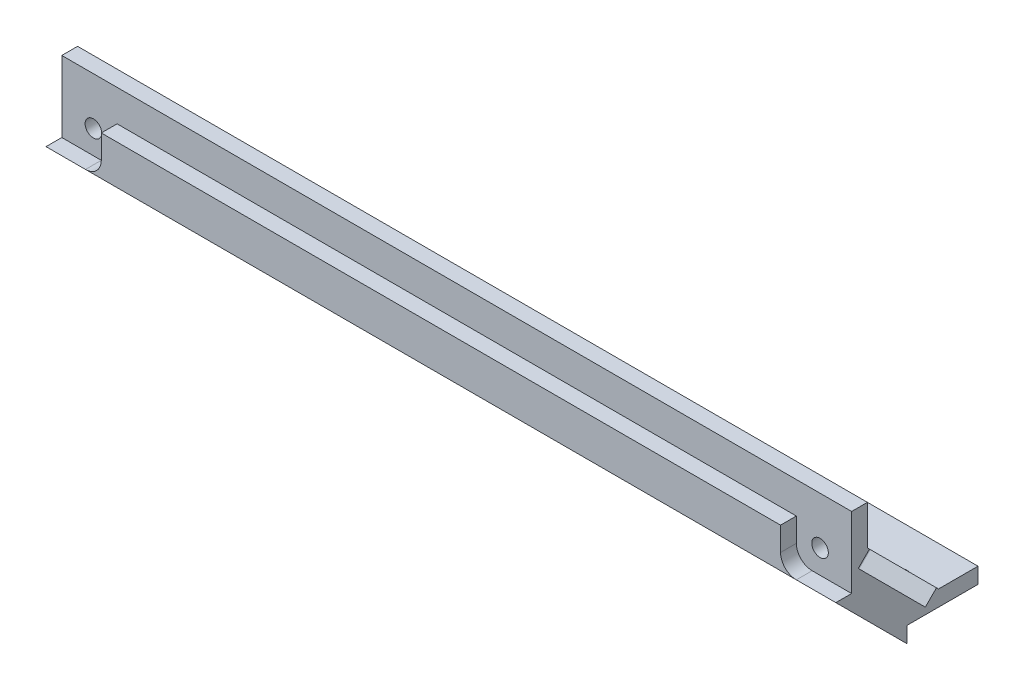
SolidWorks part; units mm, degrees
ref_plane "Front Plane" through (0, 0, 0) normal (0, 0, 1) x (1, 0, 0)
ref_plane "Top Plane" through (0, 0, 0) normal (0, 1, 0) x (1, 0, 0)
ref_plane "Right Plane" through (0, 0, 0) normal (1, 0, 0) x (0, 0, -1)
sketch "Sketch5" plane through (0, 0, 0) normal (1, 0, 0) x (0, 0, -1)
  line L0 (0, 0) -> (0, 36)
  line L1 (0, 36) -> (8, 36)
  line L5 (36, 8) -> (36, 0)
  line L6 (36, 0) -> (0, 0)
  line L7 (8, 36) -> (8, 8)
  line L8 (8, 8) -> (36, 8)
  dimension "D1" = 8
  dimension "D2" = 8
  dimension "D3" = 36
  dimension "D4" = 36
extrude "Boss-Extrude3" add sketch "Sketch5" along normal blind 200
chamfer "Chamfer2" distance 18 angle 45 1 edges at (100, 8, -8)
chamfer "Chamfer3" distance 18 angle 45 1 edges at (100, 0, 0)
sketch "Sketch6" plane through (0, 0, 0) normal (0, -1, 0) x (-1, 0, 0)
  line L1 (-200, 28) -> (0, 28)
  line L2 (-200, 28) -> (-200, 36)
  line L3 (-200, 36) -> (0, 36)
  line L4 (0, 28) -> (0, 36)
  dimension "D1" = 8
extrude "Cut-Extrude2" cut sketch "Sketch6" against normal blind 4
sketch "Sketch7" plane through (0, 0, 0) normal (0, 0, 1) x (1, 0, 0)
  line L1 (200, 36) -> (0, 36)
  line L2 (200, 36) -> (200, 28)
  line L3 (200, 28) -> (0, 28)
  line L4 (0, 36) -> (0, 28)
  dimension "D1" = 8
extrude "Cut-Extrude3" cut sketch "Sketch7" against normal blind 4
sketch "Sketch8" plane through (0, 17, -17) normal (0, 0.7071, -0.7071) x (-1, 0, 0)
  line L0 (-182.5, 0) -> (-167.5, 0) construction
  circle A0 centre (-182.5, 0) radius 1.4
  circle A1 centre (-167.5, 0) radius 1.4
  circle A2 centre (-152.5, 0) radius 1.4
  circle A3 centre (-137.5, 0) radius 1.4
  circle A4 centre (-122.5, 0) radius 1.4
  circle A5 centre (-107.5, 0) radius 1.4
  circle A6 centre (-92.5, 0) radius 1.4
  circle A7 centre (-77.5, 0) radius 1.4
  circle A8 centre (-62.5, 0) radius 1.4
  circle A9 centre (-47.5, 0) radius 1.4
  circle A10 centre (-32.5, 0) radius 1.4
  circle A11 centre (-17.5, 0) radius 1.4
  dimension "D1" = 2.8
  dimension "D2" = 182.5
  dimension "D4" = 15
  dimension "D3" = 12
extrude "Cut-Extrude4" cut sketch "Sketch8" against normal blind 3
sketch "Sketch9" plane through (0, 17, -17) normal (0, 0.7071, -0.7071) x (-1, 0, 0)
  circle A0 centre (-73, -10) radius 2.1
  circle A1 centre (-127, -10) radius 2.1
  circle A2 centre (-127, 10) radius 2.1
  circle A3 centre (-73, 10) radius 2.1
  dimension "D1" = 4.2
  dimension "D2" = 54
  dimension "D3" = 73
  dimension "D4" = 10
  dimension "D5" = 20
extrude "Cut-Extrude5" cut sketch "Sketch9" against normal blind 6
sketch "Sketch10" plane through (0, 17, -17) normal (0, 0.7071, -0.7071) x (-1, 0, 0)
  circle A0 centre (-89, -10) radius 2.1
  circle A1 centre (-111, -10) radius 2.1
  circle A2 centre (-111, 10) radius 2.1
  circle A3 centre (-89, 10) radius 2.1
  dimension "D3" = 4.2
  dimension "D1" = 22
  dimension "D2" = 20
  dimension "D4" = 10
  dimension "D5" = 89
extrude "Cut-Extrude6" cut sketch "Sketch10" against normal blind 6
sketch "Sketch11" plane through (0, 17, -17) normal (0, 0.7071, -0.7071) x (-1, 0, 0)
  line L0 (0, -12) -> (-14, 0)
  line L1 (-14, 0) -> (0, 12)
  line L2 (0, 12) -> (0, -12)
  line L3 (-200, 12) -> (-186, 0)
  line L4 (-186, 0) -> (-200, -12)
  line L5 (-200, -12) -> (-200, 12)
  dimension "D1" = 14
  dimension "D2" = 12
  dimension "D3" = 12
  dimension "D4" = 12
  dimension "D5" = 12
  dimension "D6" = 12
  dimension "D7" = 12
  dimension "D8" = 14
extrude "Cut-Extrude7" cut sketch "Sketch11" against normal blind 4
sketch "Sketch12" plane through (200, 0, 0) normal (1, 0, 0) x (0, 0, -1)
  line L1 (0, 28) -> (4, 28)
  line L2 (0, 28) -> (0, 18)
  line L3 (0, 18) -> (4, 18)
  line L4 (4, 28) -> (4, 18)
  line L5 (28, 0) -> (18, 0)
  line L6 (28, 0) -> (28, 4)
  line L7 (28, 4) -> (18, 4)
  line L8 (18, 0) -> (18, 4)
  dimension "D1" = 4
  dimension "D2" = 10
  dimension "D3" = 10
  dimension "D4" = 4
extrude "Cut-Extrude8" cut sketch "Sketch12" against normal blind 14
fillet "Fillet1" radius 4 2 edges at (14, 15.5858, -15.5858) (186, 15.5858, -15.5858)
fillet "Fillet2" radius 4 2 edges at (186, 2, -18) (186, 18, -2)
sketch "Sketch13" plane through (0, 0, 0) normal (-1, 0, 0) x (0, 0, 1)
  line L1 (-4, 28) -> (0, 28)
  line L2 (-4, 28) -> (-4, 18)
  line L3 (-4, 18) -> (0, 18)
  line L4 (0, 28) -> (0, 18)
  line L5 (-28, 0) -> (-18, 0)
  line L6 (-28, 0) -> (-28, 4)
  line L7 (-28, 4) -> (-18, 4)
  line L8 (-18, 0) -> (-18, 4)
  dimension "D1" = 4
  dimension "D2" = 10
extrude "Cut-Extrude9" cut sketch "Sketch13" against normal blind 14
fillet "Fillet3" radius 4 2 edges at (14, 2, -18) (14, 18, -2)
sketch "Sketch14" plane through (0, 0, -4) normal (0, 0, 1) x (1, 0, 0)
  circle A0 centre (192, 24) radius 2.1
  circle A1 centre (8, 24) radius 2.1
  dimension "D1" = 4.2
  dimension "D2" = 8
  dimension "D3" = 8
  dimension "D4" = 24
extrude "Cut-Extrude10" cut sketch "Sketch14" against normal blind 4
sketch "Sketch15" plane through (0, 4, 0) normal (0, -1, 0) x (-1, 0, 0)
  circle A0 centre (-8, 24) radius 2.1
  circle A1 centre (-192, 24) radius 2.1
  dimension "D4" = 4.2
  dimension "D1" = 24
  dimension "D2" = 8
  dimension "D3" = 8
extrude "Cut-Extrude11" cut sketch "Sketch15" against normal blind 4
sketch "Sketch16" plane through (0, 14.1716, -14.1716) normal (0, 0.7071, -0.7071) x (-1, 0, 0)
  circle A0 centre (-6, 0) radius 2.1
  circle A1 centre (-194, 0) radius 2.1
  dimension "D1" = 4.2
  dimension "D2" = 4.2
  dimension "D3" = 6
  dimension "D4" = 6
extrude "Cut-Extrude12" cut sketch "Sketch16" against normal blind 4
